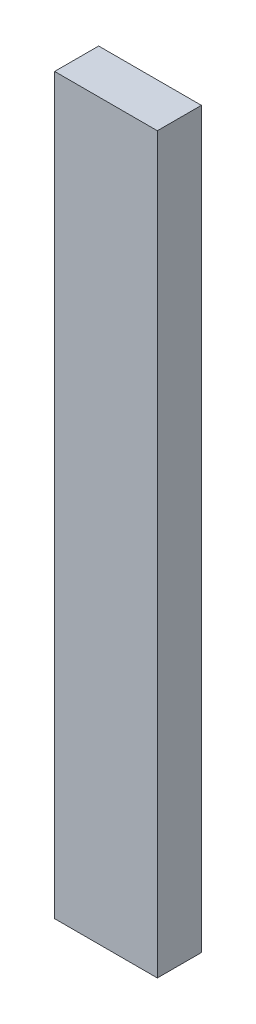
SolidWorks part; units mm, degrees
material "Pine"
ref_plane "Front Plane" through (0, 0, 0) normal (0, 0, 1) x (1, 0, 0)
ref_plane "Top Plane" through (0, 0, 0) normal (0, 1, 0) x (1, 0, 0)
ref_plane "Right Plane" through (0, 0, 0) normal (1, 0, 0) x (0, 0, -1)
sketch "Sketch1" plane through (0, 0, 0) normal (0, 1, 0) x (1, 0, 0)
  line L1 (0, 0) -> (88.9, 0)
  line L2 (0, 0) -> (0, 38.1)
  line L3 (0, 38.1) -> (88.9, 38.1)
  line L4 (88.9, 0) -> (88.9, 38.1)
  dimension "D1" = 88.9
  dimension "D2" = 38.1
extrude "Boss-Extrude1" add sketch "Sketch1" along normal blind 635
